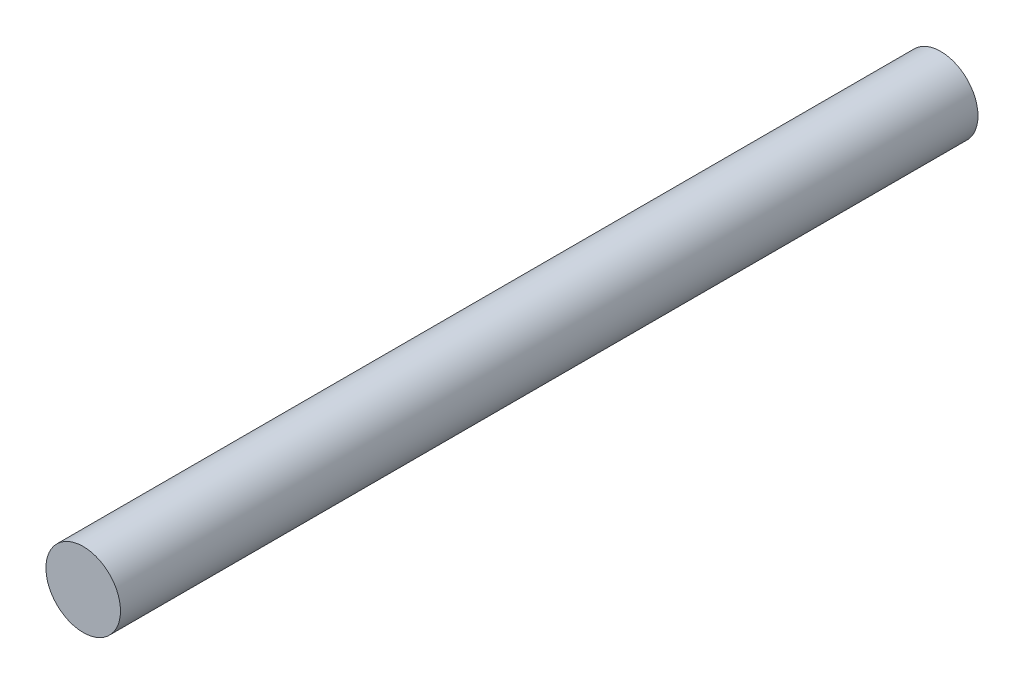
SolidWorks part; units mm, degrees
ref_plane "Front Plane" through (0, 0, 0) normal (0, 0, 1) x (1, 0, 0)
ref_plane "Top Plane" through (0, 0, 0) normal (0, 1, 0) x (1, 0, 0)
ref_plane "Right Plane" through (0, 0, 0) normal (1, 0, 0) x (0, 0, -1)
sketch "Sketch1" plane through (0, 0, 0) normal (0, 0, 1) x (1, 0, 0)
  circle A0 centre (0, 0) radius 1
extrude "Boss-Extrude1" add sketch "Sketch1" along normal blind 23 contours A0
